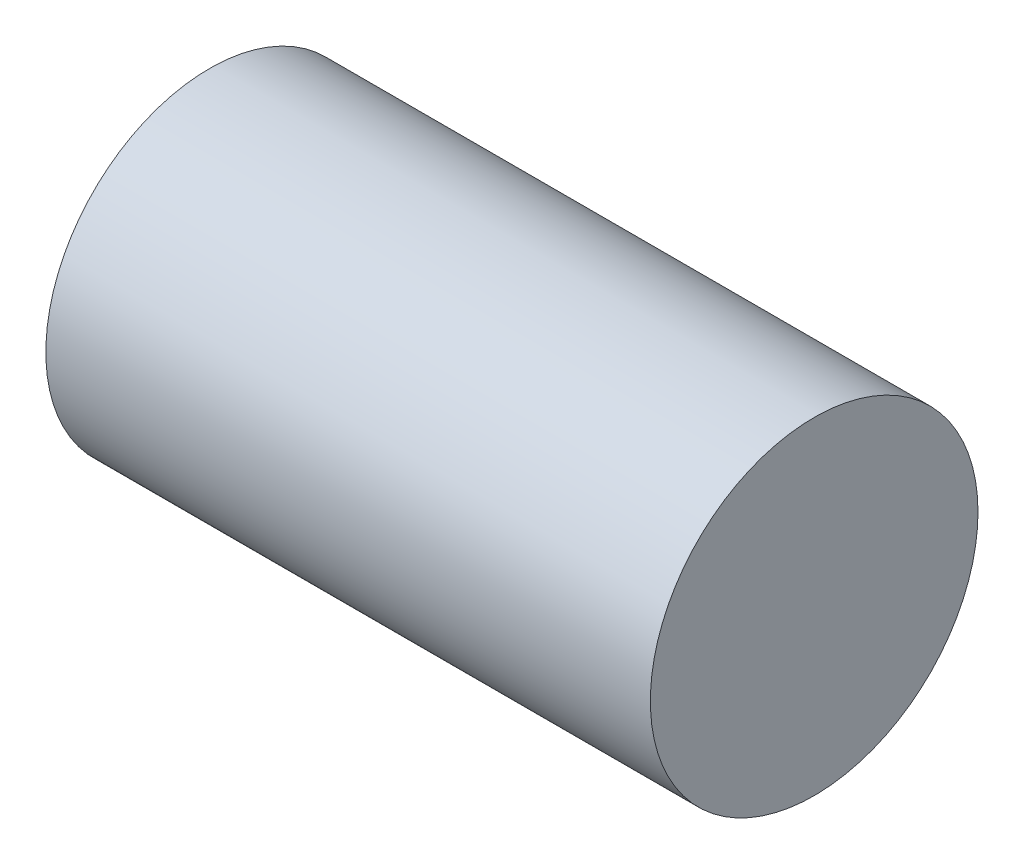
SolidWorks part; units mm, degrees
ref_plane "Front Plane" through (0, 0, 0) normal (1, 0, 0) x (0, 1, 0)
ref_plane "Top Plane" through (0, 0, 0) normal (0, 0, 1) x (0, 1, 0)
ref_plane "Right Plane" through (0, 0, 0) normal (0, 1, 0) x (-1, 0, 0)
sketch "Sketch1" plane through (0, 0, 0) normal (1, 0, 0) x (0, 1, 0)
  circle A0 centre (0, 0) radius 3.97
  dimension "D1" = 7.94
extrude "Boss-Extrude1" add sketch "Sketch1" along normal blind 14.65 contours A0
